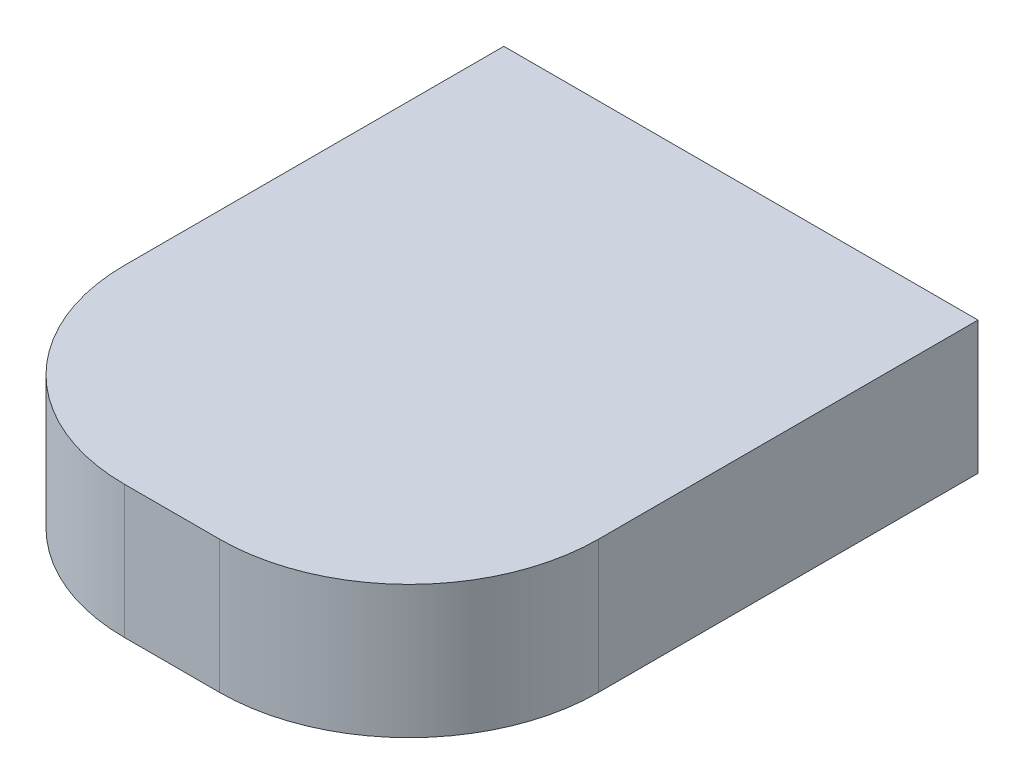
SolidWorks part; units mm, degrees
ref_plane "Front Plane" through (0, 0, 0) normal (0, 0, 1) x (1, 0, 0)
ref_plane "Top Plane" through (0, 0, 0) normal (0, 1, 0) x (1, 0, 0)
ref_plane "Right Plane" through (0, 0, 0) normal (1, 0, 0) x (0, 0, -1)
sketch "Sketch1" plane through (0, 0, 0) normal (0, 1, 0) x (1, 0, 0)
  line L1 (12.5, 15) -> (-12.5, 15)
  line L2 (12.5, 15) -> (12.5, -15)
  line L3 (12.5, -15) -> (-12.5, -15)
  line L4 (-12.5, 15) -> (-12.5, -15)
  line L5 (12.5, 15) -> (-12.5, -15) construction
  line L6 (12.5, -15) -> (-12.5, 15) construction
  point P0 (0, 0)
  dimension "D1" = 30
  dimension "D2" = 25
extrude "Boss-Extrude1" add sketch "Sketch1" along normal blind 7
sketch "Sketch2" plane through (0, 0, 0) normal (0, 1, 0) x (1, 0, 0)
  line L0 (0, 0) -> (0, -16.406) construction
  line L1 (12.5, 15) -> (-12.5, 15) construction
  circle A0 centre (0, -3) radius 10
  dimension "D1" = 20
  dimension "D2" = 18
extrude "Cut-Extrude1" cut sketch "Sketch2" along normal blind 3
fillet "Fillet1" radius 10 1 edges at (-12.5, 3.5, 15)
fillet "Fillet2" radius 10 1 edges at (12.5, 3.5, 15)
